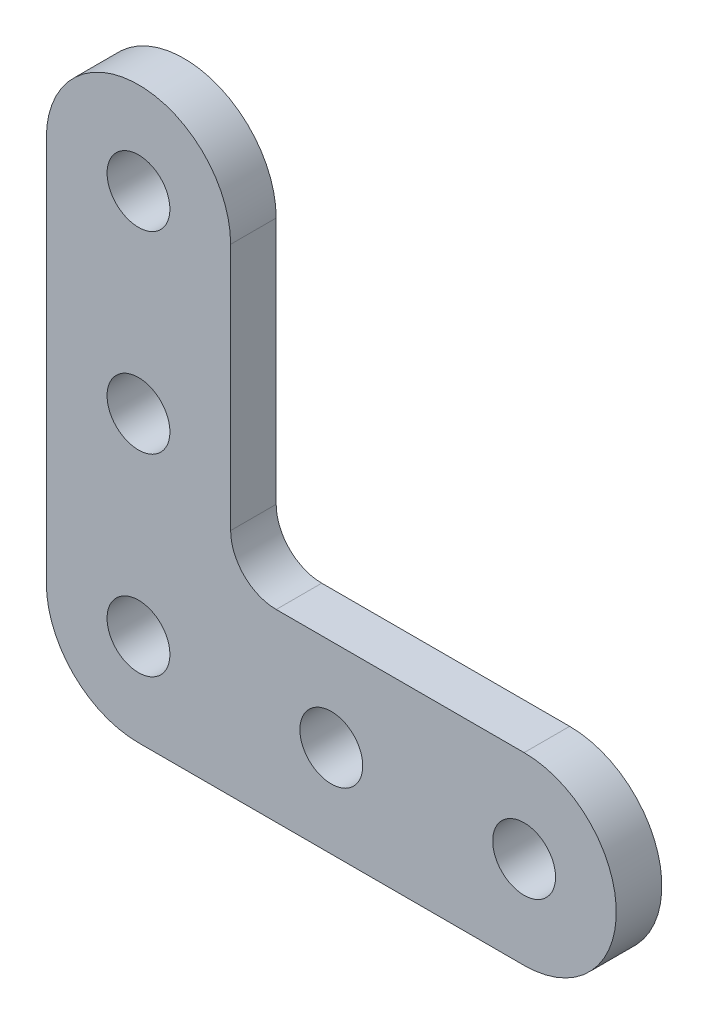
SolidWorks part; units mm, degrees
ref_plane "Front Plane" through (0, 0, 0) normal (0, 0, 1) x (1, 0, 0)
ref_plane "Top Plane" through (0, 0, 0) normal (0, 1, 0) x (1, 0, 0)
ref_plane "Right Plane" through (0, 0, 0) normal (1, 0, 0) x (0, 0, -1)
sketch "Sketch1" plane through (0, 0, 0) normal (0, 0, 1) x (1, 0, 0)
  line L0 (0, 0) -> (0, 25.4) construction
  line L1 (0, 25.4) -> (25.4, 0) construction
  line L2 (25.4, 0) -> (0, 0) construction
  line L3 (-6.07, 25.4) -> (-6.07, 0)
  line L4 (0, -6.07) -> (25.4, -6.07)
  line L5 (6.07, 25.4) -> (6.07, 0)
  line L6 (25.4, 6.07) -> (6.07, 6.07)
  circle A0 centre (0, 0) radius 2.07
  circle A1 centre (25.4, 0) radius 2.07
  circle A2 centre (0, 25.4) radius 2.07
  circle A3 centre (0, 12.7) radius 2.07
  circle A4 centre (12.7, 0) radius 2.07
  circle A5 centre (0, 25.4) radius 6.07
  circle A6 centre (0, 0) radius 6.07
  circle A7 centre (25.4, 0) radius 6.07
  dimension "D2" = 4.14
  dimension "D1" = 25.4
  dimension "D3" = 4
extrude "Boss-Extrude1" add sketch "Sketch1" along normal mid plane 3 contours A6 L5 A5 L3 A3 | A5 A2 | A6 A0 | A7 L6 L5 A6 L4 A4 | A7 A1
fillet "Fillet1" radius 3 1 edges at (6.07, 6.07, 0)
